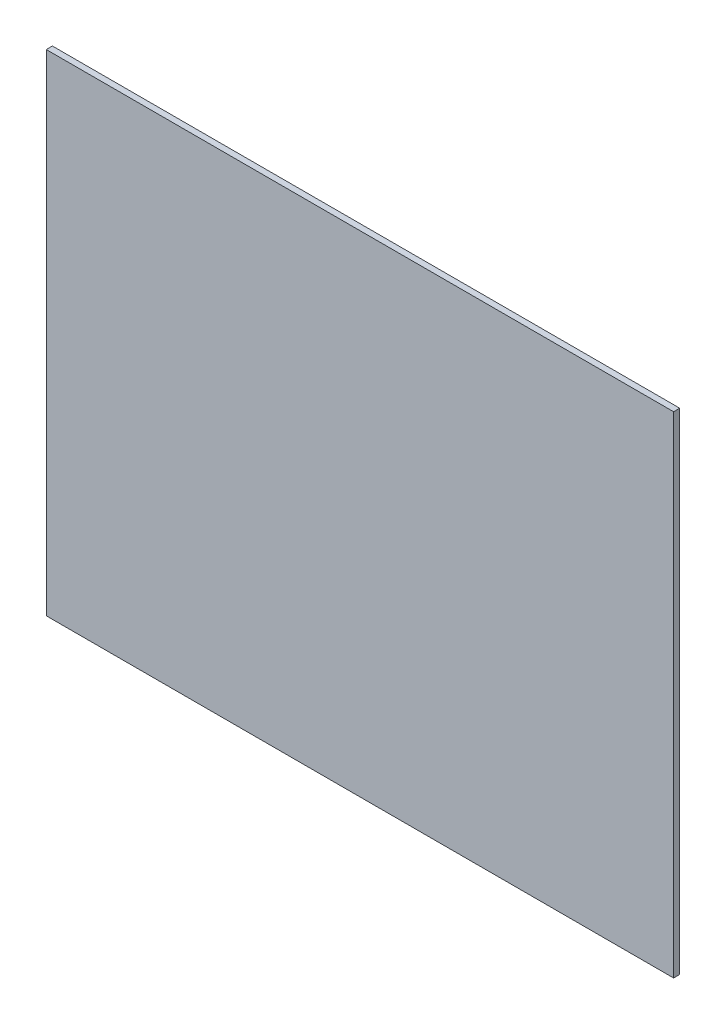
SolidWorks part; units mm, degrees
ref_plane "Front Plane" through (0, 0, 0) normal (0, 0, 1) x (1, 0, 0)
ref_plane "Top Plane" through (0, 0, 0) normal (0, 1, 0) x (1, 0, 0)
ref_plane "Right Plane" through (0, 0, 0) normal (1, 0, 0) x (0, 0, -1)
sketch "Sketch1" plane through (0, 0, 0) normal (0, 0, 1) x (1, 0, 0)
  line L1 (-350, -294) -> (350, -294)
  line L2 (-350, -294) -> (-350, 294)
  line L3 (-350, 294) -> (350, 294)
  line L4 (350, -294) -> (350, 294)
  line L5 (-350, -294) -> (350, 294) construction
  line L6 (-350, 294) -> (350, -294) construction
  point P0 (0, 0)
  dimension "D1" = 588
  dimension "D2" = 700
extrude "Boss-Extrude1" add sketch "Sketch1" along normal blind 6
fillet "Fillet1" radius 20 4 edges at (-350, 294, 3) (350, 294, 3) (350, -294, 3) (-350, -294, 3)
sketch "Sketch2" plane through (0, 0, 6) normal (0, 0, 1) x (1, 0, 0)
  line L0 (-350, 274) -> (-350, -274) construction
  line L1 (-188, -208) -> (228, -208)
  line L2 (-188, -208) -> (-188, 208)
  line L3 (-188, 208) -> (228, 208)
  line L4 (228, -208) -> (228, 208)
  line L5 (-188, -220) -> (228, -220) construction
  line L13 (-188, 104) -> (-136, 104)
  line L14 (-188, 208) -> (-136, 208)
  line L15 (-188, 208) -> (-188, 156)
  line L16 (-188, 156) -> (-136, 156)
  line L17 (-136, 208) -> (-136, 156)
  line L18 (-136, 156) -> (-136, 104)
  line L19 (-188, 52) -> (-136, 52)
  line L20 (-136, 104) -> (-136, 52)
  line L21 (-188, 0) -> (-136, 0)
  line L22 (-136, 52) -> (-136, 0)
  line L23 (-188, -52) -> (-136, -52)
  line L24 (-136, 0) -> (-136, -52)
  line L25 (-188, -104) -> (-136, -104)
  line L26 (-136, -52) -> (-136, -104)
  line L27 (-188, -156) -> (-136, -156)
  line L28 (-136, -104) -> (-136, -156)
  line L29 (-188, -208) -> (-136, -208)
  line L30 (-136, -156) -> (-136, -208)
  line L31 (-136, 156) -> (-84, 156)
  line L32 (-84, 208) -> (-84, 156)
  line L33 (-136, 104) -> (-84, 104)
  line L34 (-84, 156) -> (-84, 104)
  line L35 (-136, 52) -> (-84, 52)
  line L36 (-84, 104) -> (-84, 52)
  line L37 (-136, 0) -> (-84, 0)
  line L38 (-84, 52) -> (-84, 0)
  line L39 (-136, -52) -> (-84, -52)
  line L40 (-84, 0) -> (-84, -52)
  line L41 (-136, -104) -> (-84, -104)
  line L42 (-84, -52) -> (-84, -104)
  line L43 (-136, -156) -> (-84, -156)
  line L44 (-84, -104) -> (-84, -156)
  line L45 (-84, -156) -> (-84, -208)
  line L46 (-84, 156) -> (-32, 156)
  line L47 (-32, 208) -> (-32, 156)
  line L48 (-84, 104) -> (-32, 104)
  line L49 (-32, 156) -> (-32, 104)
  line L50 (-84, 52) -> (-32, 52)
  line L51 (-32, 104) -> (-32, 52)
  line L52 (-84, 0) -> (-32, 0)
  line L53 (-32, 52) -> (-32, 0)
  line L54 (-84, -52) -> (-32, -52)
  line L55 (-32, 0) -> (-32, -52)
  line L56 (-84, -104) -> (-32, -104)
  line L57 (-32, -52) -> (-32, -104)
  line L58 (-84, -156) -> (-32, -156)
  line L59 (-32, -104) -> (-32, -156)
  line L60 (-32, -156) -> (-32, -208)
  line L61 (-32, 156) -> (20, 156)
  line L62 (20, 208) -> (20, 156)
  line L63 (-32, 104) -> (20, 104)
  line L64 (20, 156) -> (20, 104)
  line L65 (-32, 52) -> (20, 52)
  line L66 (20, 104) -> (20, 52)
  line L67 (-32, 0) -> (20, 0)
  line L68 (20, 52) -> (20, 0)
  line L69 (-32, -52) -> (20, -52)
  line L70 (20, 0) -> (20, -52)
  line L71 (-32, -104) -> (20, -104)
  line L72 (20, -52) -> (20, -104)
  line L73 (-32, -156) -> (20, -156)
  line L74 (20, -104) -> (20, -156)
  line L75 (20, -156) -> (20, -208)
  line L76 (20, 156) -> (72, 156)
  line L77 (72, 208) -> (72, 156)
  line L78 (20, 104) -> (72, 104)
  line L79 (72, 156) -> (72, 104)
  line L80 (20, 52) -> (72, 52)
  line L81 (72, 104) -> (72, 52)
  line L82 (20, 0) -> (72, 0)
  line L83 (72, 52) -> (72, 0)
  line L84 (20, -52) -> (72, -52)
  line L85 (72, 0) -> (72, -52)
  line L86 (20, -104) -> (72, -104)
  line L87 (72, -52) -> (72, -104)
  line L88 (20, -156) -> (72, -156)
  line L89 (72, -104) -> (72, -156)
  line L90 (72, -156) -> (72, -208)
  line L91 (72, 156) -> (124, 156)
  line L92 (124, 208) -> (124, 156)
  line L93 (72, 104) -> (124, 104)
  line L94 (124, 156) -> (124, 104)
  line L95 (72, 52) -> (124, 52)
  line L96 (124, 104) -> (124, 52)
  line L97 (72, 0) -> (124, 0)
  line L98 (124, 52) -> (124, 0)
  line L99 (72, -52) -> (124, -52)
  line L100 (124, 0) -> (124, -52)
  line L101 (72, -104) -> (124, -104)
  line L102 (124, -52) -> (124, -104)
  line L103 (72, -156) -> (124, -156)
  line L104 (124, -104) -> (124, -156)
  line L105 (124, -156) -> (124, -208)
  line L106 (124, 156) -> (176, 156)
  line L107 (176, 208) -> (176, 156)
  line L108 (124, 104) -> (176, 104)
  line L109 (176, 156) -> (176, 104)
  line L110 (124, 52) -> (176, 52)
  line L111 (176, 104) -> (176, 52)
  line L112 (124, 0) -> (176, 0)
  line L113 (176, 52) -> (176, 0)
  line L114 (124, -52) -> (176, -52)
  line L115 (176, 0) -> (176, -52)
  line L116 (124, -104) -> (176, -104)
  line L117 (176, -52) -> (176, -104)
  line L118 (124, -156) -> (176, -156)
  line L119 (176, -104) -> (176, -156)
  line L120 (176, -156) -> (176, -208)
  line L121 (176, 156) -> (228, 156)
  line L122 (228, 208) -> (228, 156)
  line L123 (176, 104) -> (228, 104)
  line L124 (228, 156) -> (228, 104)
  line L125 (176, 52) -> (228, 52)
  line L126 (228, 104) -> (228, 52)
  line L127 (176, 0) -> (228, 0)
  line L128 (228, 52) -> (228, 0)
  line L129 (176, -52) -> (228, -52)
  line L130 (228, 0) -> (228, -52)
  line L131 (176, -104) -> (228, -104)
  line L132 (228, -52) -> (228, -104)
  line L133 (176, -156) -> (228, -156)
  line L134 (228, -104) -> (228, -156)
  line L135 (228, -156) -> (228, -208)
  line L137 (-193, -208) -> (-193, 208) construction
  line L138 (330, 294) -> (-330, 294) construction
  circle A41 centre (-252, -155.5) radius 13
  circle A42 centre (-220, -178) radius 15
  circle A43 centre (-220, -133) radius 15
  circle A44 centre (-220, -88) radius 15
  circle A45 centre (-220, -43) radius 15
  circle A46 centre (-220, 2) radius 15
  circle A47 centre (-220, 47) radius 15
  circle A48 centre (-220, 92) radius 15
  circle A49 centre (-220, 137) radius 15
  circle A50 centre (-220, 182) radius 15
  circle A51 centre (-252, -110.5) radius 13
  circle A52 centre (-252, -65.5) radius 13
  circle A53 centre (-252, -20.5) radius 13
  circle A54 centre (-252, 24.5) radius 13
  circle A55 centre (-252, 69.5) radius 13
  circle A56 centre (-252, 114.5) radius 13
  circle A57 centre (-252, 159.5) radius 13
  circle A58 centre (260, -178) radius 15
  circle A59 centre (292, 159.5) radius 13
  circle A60 centre (292, 114.5) radius 13
  circle A61 centre (292, 69.5) radius 13
  circle A62 centre (292, 24.5) radius 13
  circle A63 centre (292, -20.5) radius 13
  circle A64 centre (292, -65.5) radius 13
  circle A65 centre (292, -110.5) radius 13
  circle A66 centre (260, 182) radius 15
  circle A67 centre (260, 137) radius 15
  circle A68 centre (260, 92) radius 15
  circle A69 centre (260, 47) radius 15
  circle A70 centre (260, 2) radius 15
  circle A71 centre (260, -43) radius 15
  circle A72 centre (260, -88) radius 15
  circle A73 centre (260, -133) radius 15
  circle A74 centre (292, -155.5) radius 13
  text T0 "A B C D E F G H" font "Calibri" height in points 26
  text T1 "1 2 3 4 5 6 7 8" font "Calibri" height in points 26
  point P258 (0, 0)
  point P259 (0, 0)
  dimension "D4" = 30
  dimension "D8" = 45
  dimension "D16" = 32
  dimension "D21" = 416
  dimension "D6" = 26
  dimension "D1" = 416
  dimension "D2" = 162
  dimension "D3" = 208
  dimension "D5" = 22.5
  dimension "D7" = 30
  dimension "D9" = 52
  dimension "D10" = 8
  dimension "D12" = 45
  dimension "D13" = 8
  dimension "D15" = 32
  dimension "D22" = 12
  dimension "D23" = 416
  dimension "D24" = 0
  dimension "D25" = 5
  dimension "D14" = 9
  dimension "D11" = 8
sketch "Sketch3" plane through (0, 0, 0) normal (0, 0, -1) x (-1, 0, 0)
  line L1 (-327, -240) -> (287, -240)
  line L2 (-327, -240) -> (-327, 240)
  line L3 (-327, 240) -> (287, 240)
  line L4 (287, -240) -> (287, 240)
  line L5 (-327, -240) -> (287, 240) construction
  line L6 (-327, 240) -> (287, -240) construction
  line L7 (-435.8063, -317.182) -> (395.8063, -317.182)
  line L8 (-435.8063, -317.182) -> (-435.8063, 317.182)
  line L9 (-435.8063, 317.182) -> (395.8063, 317.182)
  line L10 (395.8063, -317.182) -> (395.8063, 317.182)
  line L11 (-435.8063, -317.182) -> (395.8063, 317.182) construction
  line L12 (-435.8063, 317.182) -> (395.8063, -317.182) construction
  point P0 (-20, 0)
  point P5 (-20, 0)
  dimension "D1" = 480
  dimension "D2" = 614
extrude "Cut-Extrude2" cut sketch "Sketch3" against normal blind 10
